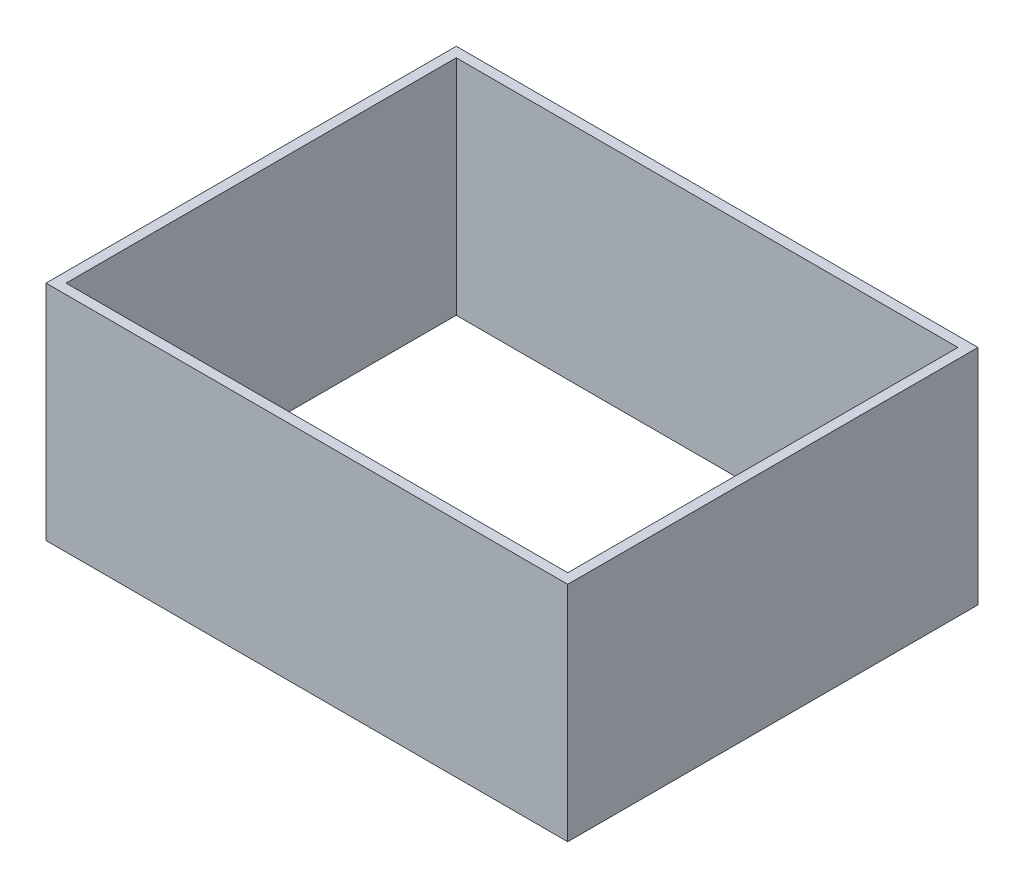
SolidWorks part; units mm, degrees
ref_plane "前视基准面" through (0, 0, 0) normal (0, 0, 1) x (1, 0, 0)
ref_plane "上视基准面" through (0, 0, 0) normal (0, 1, 0) x (1, 0, 0)
ref_plane "右视基准面" through (0, 0, 0) normal (1, 0, 0) x (0, 0, -1)
sketch "草图1" plane through (0, 0, 0) normal (0, 1, 0) x (1, 0, 0)
  line L0 (5.0769, 18) -> (5.0769, -718)
  line L1 (23.0769, 0) -> (923.0769, 0)
  line L2 (23.0769, 0) -> (23.0769, -700)
  line L3 (23.0769, -700) -> (923.0769, -700)
  line L4 (923.0769, 0) -> (923.0769, -700)
  line L5 (5.0769, -718) -> (941.0769, -718)
  line L6 (941.0769, 18) -> (941.0769, -718)
  line L7 (5.0769, 18) -> (941.0769, 18)
  dimension "D1" = 900
  dimension "D2" = 700
  dimension "D3" = 18
extrude "凸台-拉伸1" add sketch "草图1" along normal blind 400
